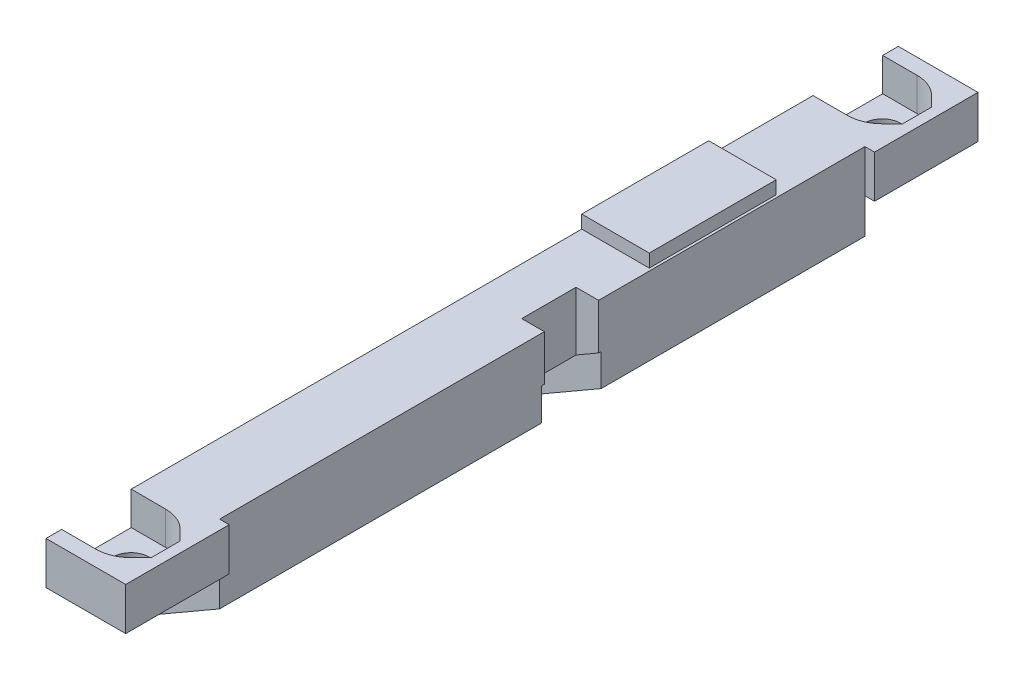
SolidWorks part; units mm, degrees
ref_plane "Front Plane" through (0, 0, 0) normal (0, 0, 1) x (1, 0, 0)
ref_plane "Top Plane" through (0, 0, 0) normal (0, 1, 0) x (1, 0, 0)
ref_plane "Right Plane" through (0, 0, 0) normal (1, 0, 0) x (0, 0, -1)
other "Configuration Table"
sketch "Sketch1" plane through (0, 0, 0) normal (0, 0, 1) x (1, 0, 0)
  line L0 (13.3671, -4) -> (17.3973, -4)
  line L1 (17.3973, -4) -> (17.3973, -8.4701)
  line L2 (17.3973, -8.4701) -> (13.3671, -10.7969)
  line L3 (13.3671, -10.7969) -> (13.3671, -4)
extrude "Clamp +X base" add sketch "Sketch1" along normal blind 37.1 from offset 20.15
sketch "Sketch2" plane through (0, 0, 0) normal (0, 0, 1) x (1, 0, 0)
  line L0 (11.1021, -12.2201) -> (19.7623, -7.2201)
  line L1 (19.7623, -7.2201) -> (18.9123, -5.7479)
  line L2 (18.9123, -5.7479) -> (10.2521, -10.7479)
  line L3 (10.2521, -10.7479) -> (11.1021, -12.2201)
extrude "Wire channel +X base Z -5.0" cut sketch "Sketch2" along normal blind 3.42 from offset 4.99
sketch "Sketch3" plane through (0, 0, 0) normal (0, 0, 1) x (1, 0, 0)
  line L0 (16.0973, -8.2207) -> (17.6973, -8.2207)
  line L1 (17.6973, -8.2207) -> (17.6973, -3.9)
  line L2 (17.6973, -3.9) -> (16.0973, -3.9)
  line L3 (16.0973, -3.9) -> (16.0973, -8.2207)
extrude "Wire notch +X base Z -5.0" cut sketch "Sketch3" along normal blind 3.12 from offset 4.84
sketch "Sketch4" plane through (0, 0, 0) normal (0, 0, 1) x (1, 0, 0)
  line L0 (13.3671, -6.45) -> (17.95, -6.45)
  line L1 (17.95, -6.45) -> (17.95, -4)
  line L2 (17.95, -4) -> (13.3671, -4)
  line L3 (13.3671, -4) -> (13.3671, -6.45)
extrude "Ear +X base -26" add sketch "Sketch4" along normal blind 5.95 from offset 26.1
sketch "Sketch5" plane through (0, 0, 0) normal (0, 0, 1) x (1, 0, 0)
  line L0 (13.3671, -6.45) -> (17.95, -6.45)
  line L1 (17.95, -6.45) -> (17.95, -4)
  line L2 (17.95, -4) -> (13.3671, -4)
  line L3 (13.3671, -4) -> (13.3671, -6.45)
extrude "Ear +X base 17" add sketch "Sketch5" along normal blind 5.95 from offset 16.95
sketch "Sketch6" plane through (0, 0, 0) normal (0, 1, 0) x (1, 0, 0)
  circle A0 centre (15.35, 23.2) radius 1.05
  circle A1 centre (15.35, -20) radius 1.05
extrude "Cut-Extrude3" cut sketch "Sketch6" along normal blind 2.65 from offset 6.55
sketch "Sketch7" plane through (0, 0, 0) normal (0, 1, 0) x (1, 0, 0)
  circle A0 centre (15.35, 23.2) radius 2
  circle A1 centre (15.35, -20) radius 2
extrude "Cut-Extrude4" cut sketch "Sketch7" along normal blind 1.92 from offset 5.91
sketch "Sketch8" plane through (0, 0, 0) normal (0, 1, 0) x (1, 0, 0)
  line L1 (13.2671, 25.2) -> (15.35, 25.2)
  line L2 (13.2671, 25.2) -> (13.2671, 21.2)
  line L3 (13.2671, 21.2) -> (15.35, 21.2)
  line L4 (15.35, 25.2) -> (15.35, 21.2)
  line L6 (13.2671, -18) -> (15.35, -18)
  line L7 (13.2671, -18) -> (13.2671, -22)
  line L8 (13.2671, -22) -> (15.35, -22)
  line L9 (15.35, -18) -> (15.35, -22)
extrude "Cut-Extrude5" cut sketch "Sketch8" along normal blind 1.92 from offset 5.91
sketch "Sketch9" plane through (0, 0, 0) normal (0, 1, 0) x (1, 0, 0)
  line L0 (15.35, 25.2) -> (16.7642, 24.6142)
  line L1 (16.7642, 24.6142) -> (17.35, 24.0284)
  line L2 (17.35, 24.0284) -> (17.35, 22.3716)
  line L3 (17.35, 22.3716) -> (16.7642, 21.7858)
  line L4 (16.7642, 21.7858) -> (15.35, 21.2)
  line L5 (15.35, 21.2) -> (15.35, 25.2)
extrude "Cut-Extrude6" cut sketch "Sketch9" along normal blind 1.92 from offset 5.91
sketch "Sketch10" plane through (0, 0, 0) normal (0, 1, 0) x (1, 0, 0)
  line L0 (15.35, -18) -> (16.7642, -18.5858)
  line L1 (16.7642, -18.5858) -> (17.35, -19.1716)
  line L2 (17.35, -19.1716) -> (17.35, -20.8284)
  line L3 (17.35, -20.8284) -> (16.7642, -21.4142)
  line L4 (16.7642, -21.4142) -> (15.35, -22)
  line L5 (15.35, -22) -> (15.35, -18)
extrude "Cut-Extrude7" cut sketch "Sketch10" along normal blind 1.92 from offset 5.91
sketch "Sketch11" plane through (0, 0, 0) normal (0, 1, 0) x (1, 0, 0)
  line L1 (13.3671, 15.2) -> (17.25, 15.2)
  line L2 (13.3671, 15.2) -> (13.3671, 7.9)
  line L3 (13.3671, 7.9) -> (17.25, 7.9)
  line L4 (17.25, 15.2) -> (17.25, 7.9)
extrude "Boss-Extrude4" add sketch "Sketch11" along normal blind 0.75 from offset 4
